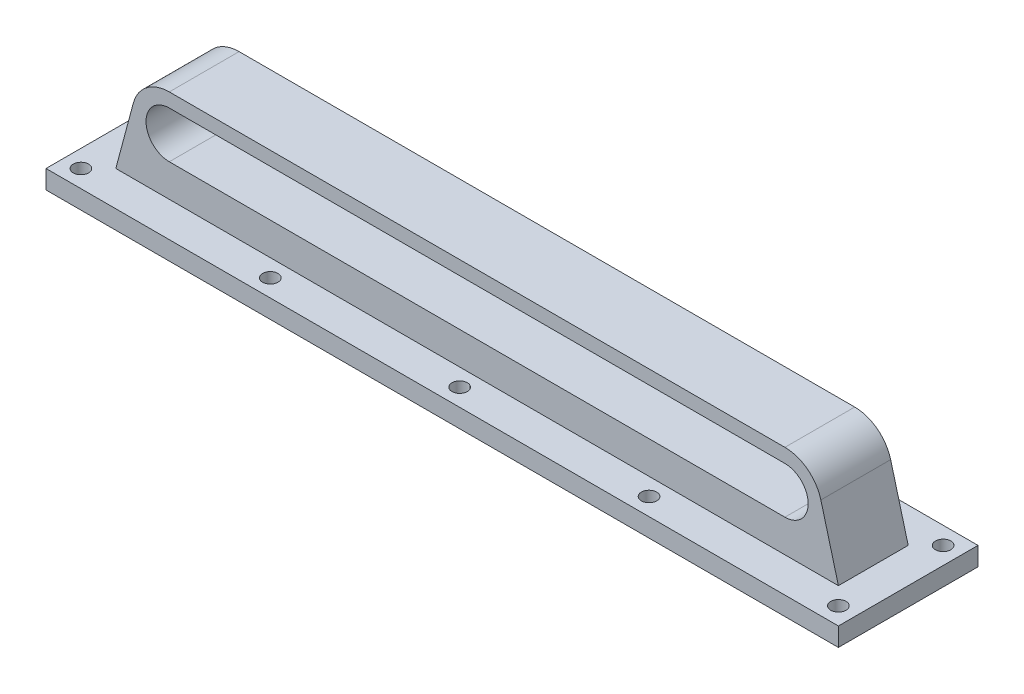
SolidWorks part; units mm, degrees
ref_plane "Front Plane" through (0, 0, 0) normal (0, 0, 1) x (1, 0, 0)
ref_plane "Top Plane" through (0, 0, 0) normal (0, 1, 0) x (1, 0, 0)
ref_plane "Right Plane" through (0, 0, 0) normal (1, 0, 0) x (0, 0, -1)
sketch "Sketch1" plane through (0, 0, 0) normal (0, 0, 1) x (1, 0, 0)
  line L0 (-132.3, 0) -> (132.3, 0) construction
  line L1 (-132.3, 10) -> (132.3, 10)
  line L2 (-132.3, -10) -> (132.3, -10)
  line L3 (-132.3, 16) -> (132.3, 16)
  line L5 (-147.7548, 4.1411) -> (-155.2952, -24)
  line L6 (-155.2952, -24) -> (-170.2952, -24)
  line L7 (-170.2952, -24) -> (-170.2952, -32)
  line L8 (-170.2952, -32) -> (170.2952, -32)
  line L9 (170.2952, -32) -> (170.2952, -24)
  line L10 (170.2952, -24) -> (155.2952, -24)
  line L11 (155.2952, -24) -> (147.7548, 4.1411)
  line L12 (0, 0) -> (0, -81.9148) construction
  line L13 (-132.3, -16) -> (132.3, -16) construction
  arc A0 (-132.3, 10) -> (-132.3, -10) centre (-132.3, 0) ccw
  arc A1 (132.3, -10) -> (132.3, 10) centre (132.3, 0) ccw
  arc A2 (147.7548, 4.1411) -> (132.3, 16) centre (132.3, 0) ccw
  arc A3 (-132.3, 16) -> (-147.7548, 4.1411) centre (-132.3, 0) ccw
  arc A5 (-132.3, 16) -> (-132.3, -16) centre (-132.3, 0) ccw construction
  arc A6 (132.3, -16) -> (132.3, 16) centre (132.3, 0) ccw construction
  point P2 (0, 0)
  point P24 (0, 0)
  point P25 (0, 0)
  point P26 (412.3148, 4.1411)
  dimension "D1" = 10
  dimension "D3" = 15
  dimension "D4" = 264.6
  dimension "D5" = 105
  dimension "D6" = 32
  dimension "D7" = 8
  dimension "D2" = 6
extrude "Boss-Extrude1" add sketch "Sketch1" along normal mid plane 30 contours L2 A1 L1 A0 | L8 L9 L10 L11 A2 L3 A3 L5 L6 L7
sketch "Sketch3" plane through (0, -32, 0) normal (0, -1, 0) x (1, 0, 0)
  line L0 (-170.2952, 15) -> (-170.2952, 30)
  line L1 (-170.2952, 30) -> (170.2952, 30)
  line L2 (170.2952, 30) -> (170.2952, 15)
  line L4 (-170.2952, -15) -> (170.2952, -15)
  line L5 (170.2952, -15) -> (170.2952, 15)
  line L6 (170.2952, 15) -> (-170.2952, 15)
  line L7 (-170.2952, 15) -> (-170.2952, -15)
  line L8 (-170.2952, -15) -> (170.2952, -15)
  line L9 (170.2952, -15) -> (170.2952, 15)
  line L10 (170.2952, 15) -> (-170.2952, 15)
  line L11 (-170.2952, 15) -> (-170.2952, -15) construction
  line L14 (-155.2952, 15) -> (-155.2952, -15) construction
  line L15 (-155.2952, 15) -> (-155.2952, -15) construction
  point P2 (-430.6226, 42)
  point P3 (0, 0)
  point P10 (0, 0)
  point P12 (0, 0)
  dimension "D2" = 15
  dimension "D3" = 15
  dimension "D1" = 0
extrude "Boss-Extrude2" add sketch "Sketch3" against normal blind 8 contours L10 L0 L1 L2
mirror "Mirror1" about plane through (0, 0, 0) normal (0, 0, 1) of "Boss-Extrude2"
sketch "Sketch4" plane through (0, -24, 0) normal (0, 1, 0) x (1, 0, 0)
  line L0 (162.7952, 22.5) -> (-162.7952, 22.5) construction
  line L1 (-162.7952, 22.5) -> (-162.7952, -22.5) construction
  line L2 (-162.7952, -22.5) -> (162.7952, -22.5) construction
  line L3 (162.7952, -22.5) -> (162.7952, 22.5) construction
  line L4 (170.2952, -30) -> (170.2952, 30)
  line L5 (170.2952, 30) -> (-170.2952, 30)
  line L6 (-170.2952, 30) -> (-170.2952, -30)
  line L7 (-170.2952, -30) -> (170.2952, -30)
  line L8 (170.2952, -30) -> (170.2952, 30) construction
  line L9 (170.2952, 30) -> (-170.2952, 30) construction
  line L10 (-170.2952, 30) -> (-170.2952, -30) construction
  line L11 (-170.2952, -30) -> (170.2952, -30) construction
  line L12 (-81.3976, -19.5) -> (-81.3976, -60.4439) construction
  line L13 (81.3976, -19.5) -> (81.3976, 19.5) construction
  point P8 (0, -22.5)
  point P9 (-162.7952, 22.5)
  point P10 (-162.7952, -22.5)
  point P11 (162.7952, -22.5)
  point P12 (162.7952, 22.5)
  point P13 (-81.3976, -22.5)
  point P14 (0, 22.5)
  point P16 (-81.3976, 22.5)
  point P20 (81.3976, -22.5)
  point P21 (81.3976, 22.5)
  point P22 (0, 0)
  point P23 (0, 0)
  point P24 (0, 0)
  dimension "D1" = 0
  dimension "D2" = 7.5
hole_wizard "M6 Clearance Hole1" positions "3DSketch1" profile "Sketch6" hole size "M6" standard "ANSI Metric" end condition through all
sketch3d "3DSketch1"
  point P0 (-162.7952, -24, -22.5)
  point P3 (-162.7952, -24, 22.5)
  point P6 (-81.3976, -24, 22.5)
  point P9 (-81.3976, -24, -22.5)
  point P12 (0, -24, 22.5)
  point P15 (0, -24, -22.5)
  point P18 (81.3976, -24, 22.5)
  point P21 (81.3976, -24, -22.5)
  point P24 (162.7952, -24, -22.5)
  point P27 (162.7952, -24, 22.5)
sketch "Sketch6" plane through (-162.7952, -24, -22.5) normal (1, 0, 0) x (0, 0, 1)
  line L0 (0, 0) -> (0, 8)
  line L1 (0, 8) -> (3.3, 8)
  line L2 (3.3, 8) -> (3.3, 0)
  line L5 (3.3, 0) -> (0, 0)
  line L11 (0, -6.35) -> (0, 107.95) construction
  dimension "Thru Hole Dia." = 6.6
  dimension "Thru Hole Depth" = 8
equation "\"D3@Sketch3\"=\"D2@Sketch3\""
